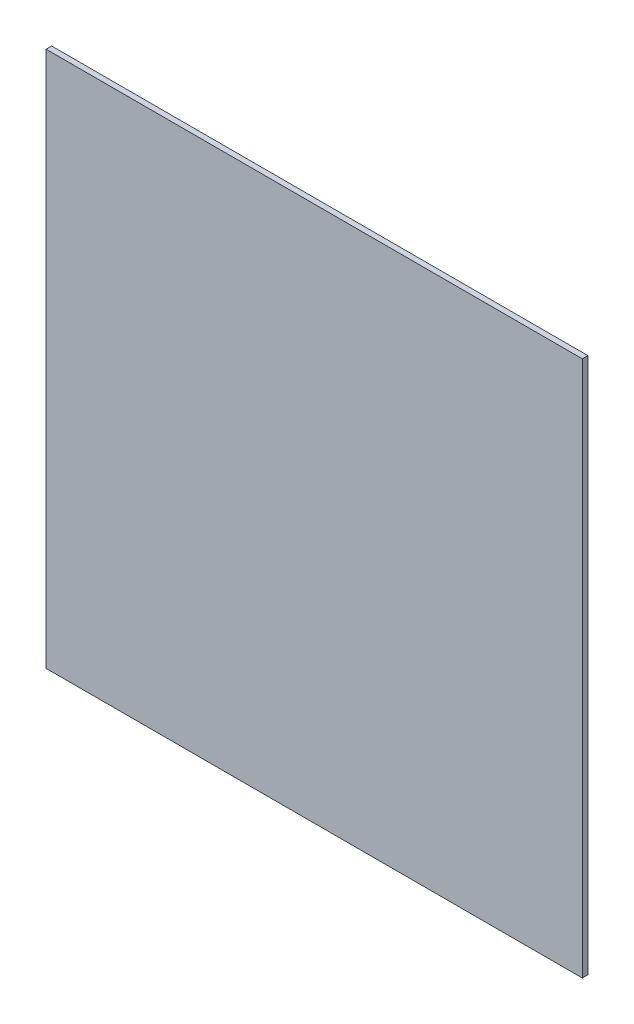
SolidWorks part; units mm, degrees
ref_plane "Front Plane" through (0, 0, 0) normal (0, 0, 1) x (1, 0, 0)
ref_plane "Top Plane" through (0, 0, 0) normal (0, 1, 0) x (1, 0, 0)
ref_plane "Right Plane" through (0, 0, 0) normal (1, 0, 0) x (0, 0, -1)
sketch "Sketch1" plane through (0, 0, 0) normal (0, 0, 1) x (1, 0, 0)
  line L1 (-304.8, -304.8) -> (304.8, -304.8)
  line L2 (-304.8, -304.8) -> (-304.8, 304.8)
  line L3 (-304.8, 304.8) -> (304.8, 304.8)
  line L4 (304.8, -304.8) -> (304.8, 304.8)
  line L5 (-304.8, -304.8) -> (304.8, 304.8) construction
  line L6 (-304.8, 304.8) -> (304.8, -304.8) construction
  point P0 (0, 0)
  dimension "D1" = 609.6
  dimension "D2" = 609.6
extrude "Boss-Extrude1" add sketch "Sketch1" along normal blind 6.35
